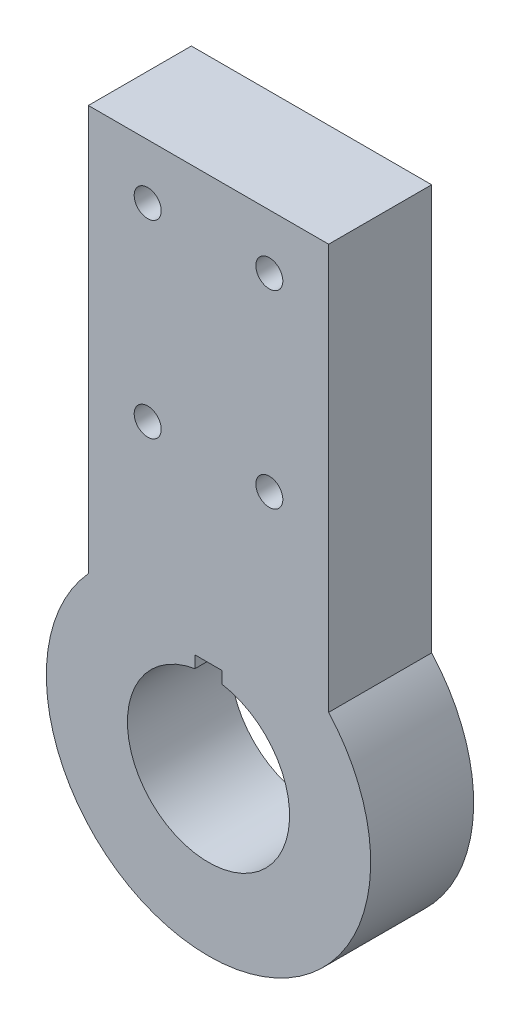
SolidWorks part; units mm, degrees
ref_plane "Front Plane" through (0, 0, 0) normal (0, 0, 1) x (1, 0, 0)
ref_plane "Top Plane" through (0, 0, 0) normal (0, 1, 0) x (1, 0, 0)
ref_plane "Right Plane" through (0, 0, 0) normal (1, 0, 0) x (0, 0, -1)
sketch "Sketch1" plane through (0, 0, 0) normal (0, 0, 1) x (1, 0, 0)
  line L2 (-22.225, 20.1507) -> (-22.225, 95.1507)
  line L3 (-22.225, 95.1507) -> (22.225, 95.1507)
  line L4 (22.225, 20.1507) -> (22.225, 95.1507)
  arc A1 (-22.225, 20.1507) -> (22.225, 20.1507) centre (0, 0) ccw
  circle A2 centre (0, 0) radius 15
  dimension "D5" = 30
  dimension "D2" = 30
  dimension "D1" = 44.45
  dimension "D6" = 75
extrude "Boss-Extrude1" add sketch "Sketch1" along normal blind 19.05
sketch "Sketch2" plane through (0, 0, 19.05) normal (0, 0, 1) x (1, 0, 0)
  line L0 (0, 0) -> (0, 17) construction
  line L1 (-2.5, 17) -> (2.5, 17)
  line L2 (2.5, 17) -> (2.5, 0)
  line L3 (2.5, 0) -> (-2.5, 0)
  line L4 (-2.5, 0) -> (-2.5, 17)
  point P8 (0, 17)
  dimension "D1" = 17
  dimension "D2" = 5
extrude "Cut-Extrude1" cut sketch "Sketch2" against normal through all
sketch "Sketch3" plane through (0, 0, 19.05) normal (0, 0, 1) x (1, 0, 0)
  line L0 (-11.25, 85) -> (-22.225, 85) construction
  line L1 (-11.25, 85) -> (11.25, 85) construction
  line L2 (-11.25, 85) -> (-11.25, 50) construction
  line L3 (-11.25, 50) -> (11.25, 50) construction
  line L4 (11.25, 85) -> (11.25, 50) construction
  line L5 (-22.225, 95.1507) -> (-22.225, 20.1507) construction
  line L6 (0, 50) -> (0, 0) construction
  circle A0 centre (-11.25, 85) radius 2.5
  circle A1 centre (11.25, 85) radius 2.5
  circle A2 centre (11.25, 50) radius 2.5
  circle A3 centre (-11.25, 50) radius 2.5
  point P5 (0, 50)
  dimension "D2" = 5
  dimension "D1" = 50
  dimension "D3" = 35
  dimension "D4" = 22.5
extrude "Cut-Extrude2" cut sketch "Sketch3" against normal through all
equation "\"tube_width\"= 1in"
equation "\"tube_height\"= 2in"
equation "\"tube_thickness\"= 0.125in"
equation "\"D1@Sketch1\"=\"tube_height\"-2*\"tube_thickness\""
equation "\"D1@Boss-Extrude1\"=\"tube_width\"-2*\"tube_thickness\""
